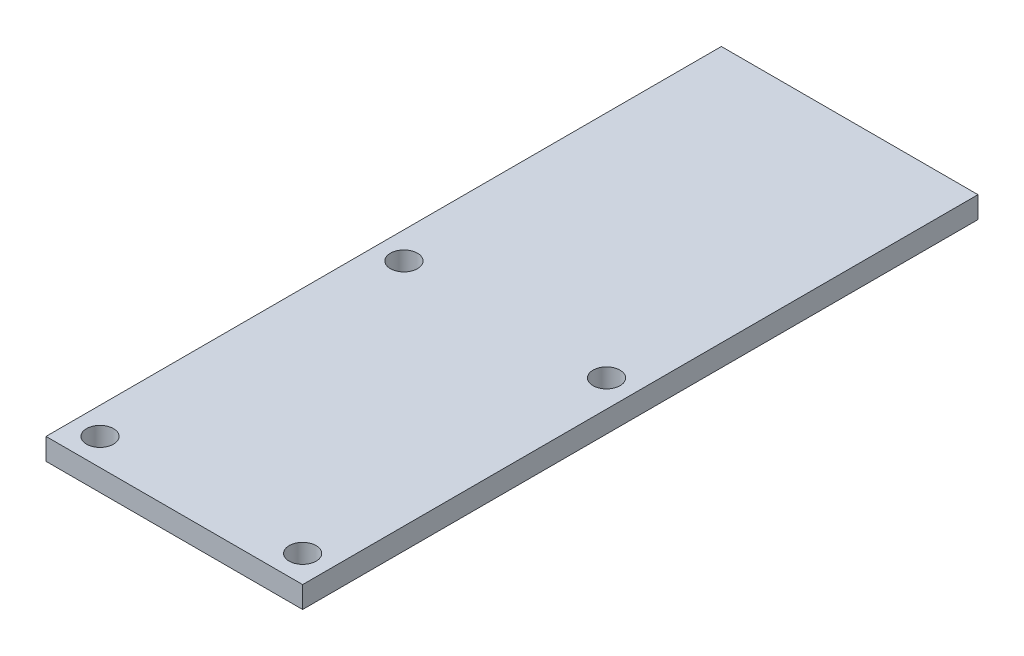
SolidWorks part; units mm, degrees
ref_plane "Front Plane" through (0, 0, 0) normal (0, 0, 1) x (1, 0, 0)
ref_plane "Top Plane" through (0, 0, 0) normal (0, 1, 0) x (1, 0, 0)
ref_plane "Right Plane" through (0, 0, 0) normal (1, 0, 0) x (0, 0, -1)
sketch "Sketch1" plane through (0, 0, 0) normal (0, 1, 0) x (1, 0, 0)
  line L0 (2, 50) -> (2, 0) construction
  line L1 (0, 0) -> (19, 0)
  line L2 (0, 0) -> (0, 50)
  line L3 (0, 50) -> (19, 50)
  line L4 (19, 0) -> (19, 50)
  line L5 (17, 50) -> (17, 0) construction
  line L6 (0, 2) -> (19, 2) construction
  line L7 (0, 24.5) -> (19, 24.5) construction
  circle A0 centre (2, 2) radius 1
  circle A1 centre (2, 24.5) radius 1
  circle A2 centre (17, 24.5) radius 1
  circle A3 centre (17, 2) radius 1
  dimension "D7" = 2
  dimension "D1" = 50
  dimension "D2" = 19
  dimension "D3" = 2
  dimension "D4" = 2
  dimension "D5" = 2
  dimension "D6" = 24.5
extrude "Boss-Extrude1" add sketch "Sketch1" along normal blind 1.6
